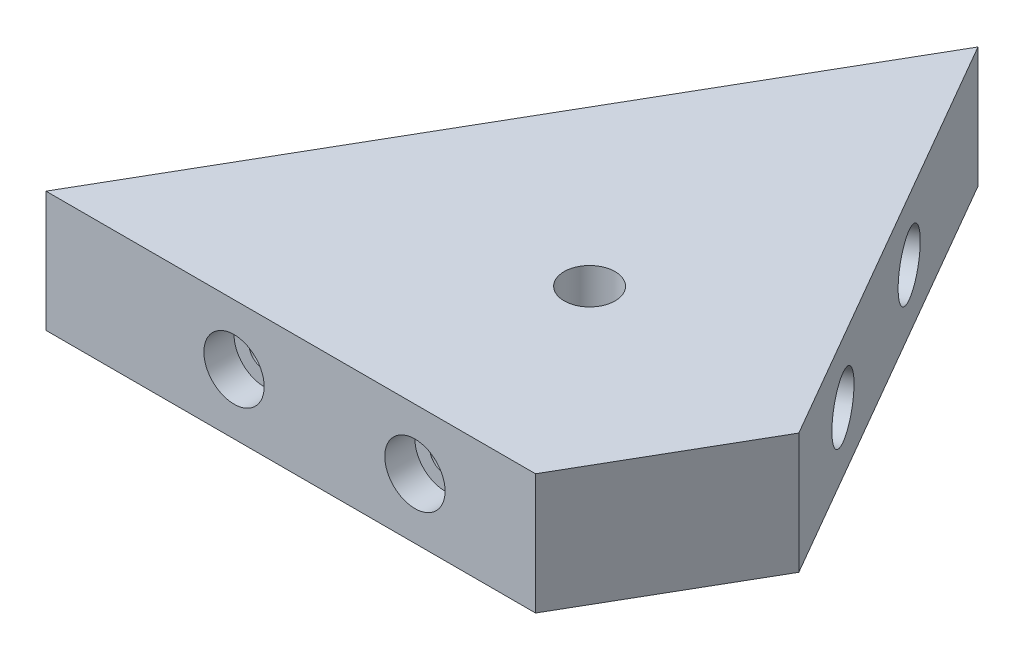
SolidWorks part; units mm, degrees
material "1023 Carbon Steel Sheet (SS)"
ref_plane "Front Plane" through (0, 0, 0) normal (0, 0, 1) x (1, 0, 0)
ref_plane "Top Plane" through (0, 0, 0) normal (0, 1, 0) x (1, 0, 0)
ref_plane "Right Plane" through (0, 0, 0) normal (1, 0, 0) x (0, 0, -1)
sketch "Sketch1" plane through (0, 0, 0) normal (0, 1, 0) x (1, 0, 0)
  line L0 (159.6594, -241.1624) -> (-297.5406, 22.8022) construction
  line L1 (-145.1406, 286.7667) -> (-449.9406, -241.1624) construction
  line L2 (-449.9406, -241.1624) -> (159.6594, -241.1624) construction
  line L3 (159.6594, -241.1624) -> (-145.1406, 286.7667) construction
  line L4 (93.6683, -241.1624) -> (93.6683, -203.0624) construction
  line L5 (119.0683, -241.1624) -> (129.2161, -223.5859)
  line L6 (55.5683, -241.1624) -> (55.5683, -181.0653) construction
  line L7 (15.9736, -241.1624) -> (51.8951, -178.9446)
  line L8 (15.9736, -241.1624) -> (119.0683, -241.1624)
  line L9 (51.8951, -178.9446) -> (129.2161, -223.5859)
  line L10 (93.6683, -203.0624) -> (55.5683, -203.0624) construction
  dimension "D1" = 609.6
  dimension "D2" = 38.1
  dimension "D3" = 25.4
  dimension "D4" = 38.1
  dimension "D6" = 40.5911
  dimension "D5" = 15.24
  dimension "D7" = 103.0947
  dimension "D8" = 60
  dimension "D9" = 120
extrude "Boss-Extrude1" add sketch "Sketch1" along normal blind 25.4
sketch "Sketch2" plane through (0, 0, 241.1624) normal (0, 0, 1) x (1, 0, 0)
  line L0 (15.9736, 0) -> (119.0683, 0) construction
  line L1 (15.9736, 0) -> (15.9736, 25.4) construction
  line L2 (119.0683, 0) -> (119.0683, 25.4) construction
  line L3 (15.9736, 25.4) -> (119.0683, 25.4) construction
  line L4 (15.9736, 0) -> (119.0683, 25.4) construction
  line L5 (119.0683, 0) -> (15.9736, 25.4) construction
  line L6 (93.6683, 25.4) -> (93.6683, 0) construction
  line L7 (55.5683, 0) -> (55.5683, 25.4) construction
  circle A0 centre (55.5683, 12.7) radius 6.35
  circle A1 centre (93.6683, 12.7) radius 6.35
  point P6 (67.521, 12.7)
  dimension "D4" = 12.7
  dimension "D5" = 12.7
  dimension "D1" = 25.4
  dimension "D2" = 25.4
  dimension "D3" = 38.1
extrude "Cut-Extrude1" cut sketch "Sketch2" against normal blind 6.35
sketch "Sketch3" plane through (0, 0, 234.8124) normal (0, 0, 1) x (1, 0, 0)
  circle A0 centre (55.5683, 12.7) radius 3.2639
  dimension "D1" = 6.5278
extrude "Cut-Extrude2" cut sketch "Sketch3" against normal blind 16.51
sketch "Sketch4" plane through (0, 0, 234.8124) normal (0, 0, 1) x (1, 0, 0)
  circle A0 centre (93.6683, 12.7) radius 3.2639
  dimension "D1" = 6.5278
extrude "Cut-Extrude3" cut sketch "Sketch4" against normal blind 16.51
mirror "Mirror1" about plane through (51.8951, 25.4, 178.9446) normal (-0.5, 0, 0.866) of "Boss-Extrude1", "Cut-Extrude1", "Cut-Extrude2", "Cut-Extrude3"
sketch "Sketch5" plane through (0, 25.4, 0) normal (0, 1, 0) x (1, 0, 0)
  line L0 (87.8165, -116.7268) -> (15.9736, -241.1624) construction
  line L1 (15.9736, -241.1624) -> (119.0683, -241.1624) construction
  line L2 (119.0683, -241.1624) -> (139.3639, -206.0094) construction
  line L3 (139.3639, -206.0094) -> (87.8165, -116.7268) construction
  line L4 (51.8951, -178.9446) -> (129.2161, -223.5859) construction
  circle A0 centre (90.5556, -201.2653) radius 5.3578
  dimension "D1" = 10.7156
extrude "Cut-Extrude4" cut sketch "Sketch5" against normal through all
ref_plane "Plane1" through (0, 0, 241.1624) normal (0, 0, 1) x (1, 0, 0)
equation "\"bplate_length\"= 24in"
equation "\"bplate_height\"= 6in"
equation "\"bplate_thickness\"= 0.5in"
equation "\"connector_plate_hole_diameter\"= 0.375in"
equation "\"connector_plate_hole_depth\"= 1in"
equation "\"connector_plate_thickness\"= 1in"
equation "\"D1@Sketch1\"=\"bplate_length\""
